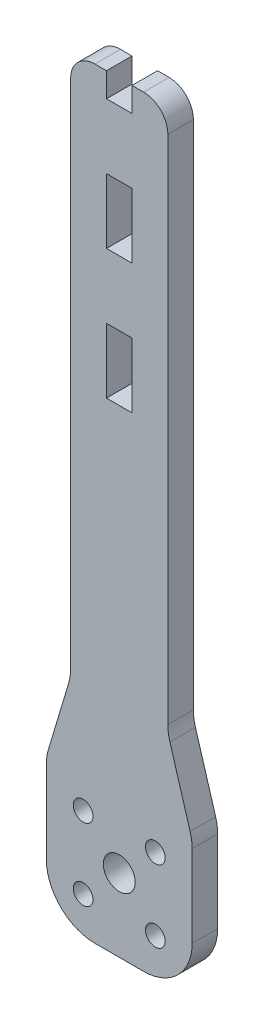
SolidWorks part; units mm, degrees
material "Hexcel AS4C (3000 Filaments)"
ref_plane "Front Plane" through (0, 0, 0) normal (0, 0, 1) x (1, 0, 0)
ref_plane "Top Plane" through (0, 0, 0) normal (0, 1, 0) x (1, 0, 0)
ref_plane "Right Plane" through (0, 0, 0) normal (1, 0, 0) x (0, 0, -1)
sketch "Sketch1" plane through (0, 0, 0) normal (0, 0, 1) x (1, 0, 0)
  line L0 (0, 10.16) -> (4, 10.16)
  line L1 (0, 0) -> (4, 0)
  line L2 (0, 0) -> (0, -10.16)
  line L3 (0, -10.16) -> (4, -10.16)
  line L4 (4, 0) -> (4, -10.16)
  line L5 (0, -20.32) -> (4, -20.32)
  line L6 (0, -20.32) -> (0, -30.48)
  line L7 (0, -30.48) -> (4, -30.48)
  line L8 (4, -20.32) -> (4, -30.48)
  line L13 (4, 10.16) -> (4, 13.97)
  line L14 (4, 13.97) -> (5.81, 13.97)
  line L15 (9.62, 10.16) -> (9.62, -70.0016)
  line L16 (0, 10.16) -> (0, 13.97)
  line L17 (0, 13.97) -> (-1.81, 13.97)
  line L18 (-5.62, 10.16) -> (-5.62, -70.0016)
  line L19 (-3.6569, -88.3231) -> (-3.6569, -99.6369) construction
  line L20 (-3.6569, -99.6369) -> (7.6569, -99.6369) construction
  line L21 (-3.6569, -99.6369) -> (7.6569, -88.3231) construction
  line L22 (-5.9414, -72.1912) -> (-9.1086, -82.7488)
  line L23 (-9.43, -84.9384) -> (-9.43, -97.79)
  line L24 (-1.81, -105.41) -> (5.81, -105.41)
  line L25 (13.43, -97.79) -> (13.43, -84.9384)
  line L26 (13.1086, -82.7488) -> (9.9414, -72.1912)
  circle A0 centre (2, -93.98) radius 2.5
  circle A1 centre (7.6569, -88.3231) radius 1.55
  circle A2 centre (-3.6569, -88.3231) radius 1.55
  circle A3 centre (-3.6569, -99.6369) radius 1.55
  circle A4 centre (7.6569, -99.6369) radius 1.55
  arc A5 (-9.1086, -82.7488) -> (-9.43, -84.9384) centre (-1.81, -84.9384) ccw
  arc A6 (-5.62, -70.0016) -> (-5.9414, -72.1912) centre (-13.24, -70.0016) cw
  arc A7 (9.62, -70.0016) -> (9.9414, -72.1912) centre (17.24, -70.0016) ccw
  arc A8 (13.43, -84.9384) -> (13.1086, -82.7488) centre (5.81, -84.9384) ccw
  arc A9 (5.81, -105.41) -> (13.43, -97.79) centre (5.81, -97.79) ccw
  arc A10 (-9.43, -97.79) -> (-1.81, -105.41) centre (-1.81, -97.79) ccw
  arc A11 (5.81, 13.97) -> (9.62, 10.16) centre (5.81, 10.16) cw
  arc A12 (-1.81, 13.97) -> (-5.62, 10.16) centre (-1.81, 10.16) ccw
  point P20 (2, -30.48)
  point P28 (2, -93.98)
  point P29 (0, 0)
  point P34 (0, 0)
  point P35 (14.7, -85.4464)
  point P38 (-9.43, -83.82)
  point P41 (-5.62, -71.12)
  point P44 (9.62, -71.12)
  point P47 (13.43, -83.82)
  point P52 (2, -105.41)
  dimension "D9" = 3.1
  dimension "D10" = 3.1
  dimension "D11" = 3.1
  dimension "D12" = 3.1
  dimension "D13" = 5
  dimension "D20" = 7.62
  dimension "D16" = 3.81
  dimension "D1" = 10.16
  dimension "D2" = 10.16
  dimension "D3" = 10.16
  dimension "D4" = 10.16
  dimension "D5" = 4
  dimension "D6" = 3.81
  dimension "D7" = 15.24
  dimension "D8" = 63.5
  dimension "D14" = 16
  dimension "D15" = 11.43
  dimension "D17" = 12.7
  dimension "D18" = 10.16
  dimension "D19" = 11.43
extrude "Boss-Extrude1" add sketch "Sketch1" along normal blind 4
